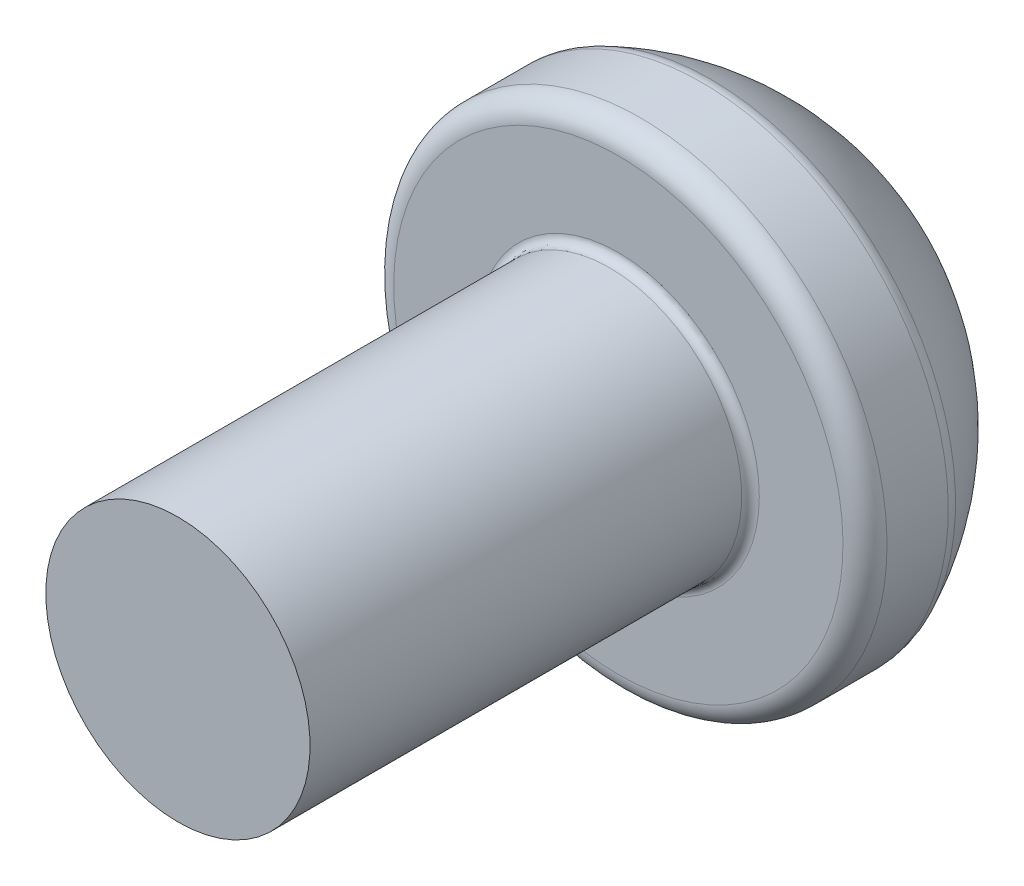
SolidWorks part; units mm, degrees
ref_plane "Plan1" through (0, 0, 0) normal (0, 0, 1) x (1, 0, 0)
ref_plane "Plan2" through (0, 0, 0) normal (0, 1, 0) x (1, 0, 0)
ref_plane "Plan3" through (0, 0, 0) normal (1, 0, 0) x (0, 0, -1)
sketch "Sketch1" plane through (0, 0, 0) normal (1, 0, 0) x (0, 0, -1)
  line L0 (2.4, 0) -> (-5, 0) construction
  line L1 (-5, 0) -> (-5, 1.5)
  line L2 (-5, 1.5) -> (0, 1.5)
  line L3 (0, 1.5) -> (0, 2.8)
  line L4 (0, 2.8) -> (1, 2.8)
  line L5 (2.4, 0) -> (2.4, 1.54)
  line L6 (2.4, 0) -> (-5, 0)
  line L7 (0, 0) -> (-0.5, 0) construction
  line L8 (0, 0) -> (0, 2.15) construction
  line L9 (0, 0) -> (0, 2.55) construction
  arc A0 (1, 2.8) -> (2.4, 1.54) centre (-0.253, 0) cw
  dimension "D1" = 3.08
  dimension "D" = 3
  dimension "L" = 5
  dimension "D2" = 1
  dimension "K" = 2.4
  dimension "DK" = 5.6
  dimension "P" = 0.5
  dimension "DW" = 5.1
revolve "Base-Revolve" add sketch "Sketch1"
cosmetic thread "Cosmetic_Thread1"
fillet "Fillet1" radius 0.1 1 edges at (0, 1.5, 0)
fillet "Fillet2" radius 0.25 2 edges at (0, 2.8, -1) (0, 2.8, 0)
hole_wizard "Hole1" positions "Sketch3" profile "Sketch2" legacy
sketch "Sketch3" plane through (0, 0, -2.4) normal (0, 0, -1) x (-1, 0, 0)
  circle A0 centre (0, 0) radius 1.54 construction
  point P0 (0, 0)
sketch "Sketch2" plane through (0, 0, -2.4) normal (1, 0, 0) x (0, 1, 0)
  line L0 (0, 0) -> (0, 1.3731)
  line L1 (0, 1.3731) -> (1.025, 1)
  line L2 (1.025, 1) -> (1.025, 0)
  line L4 (1.025, 0) -> (0, 0)
  line L6 (0, 1.3731) -> (-1.025, 1) construction
  line L7 (0, -4.2442) -> (0, 117.3081) construction
  dimension "Diameter" = 2.05
  dimension "Depth" = 1
  dimension "Drill Angle" = 140
sketch "Sketch4" plane through (0, 0, -2.4) normal (0, 0, -1) x (-1, 0, 0)
  line L0 (0, 1.4) -> (0, -1.4) construction
  line L1 (0, 0) -> (0.8075, -1.3986) construction
  line L2 (0, 0) -> (-0.8075, -1.3986) construction
  line L3 (0, 0) -> (-1.615, 0) construction
  line L4 (0, 0) -> (-0.8075, 1.3986) construction
  line L5 (0, 0) -> (0.8075, 1.3986) construction
  line L6 (0, 0) -> (1.615, 0) construction
  arc A0 (1.0888, -0.88) -> (1.3065, -0.5029) centre (0, 0) ccw
  arc A1 (1.0888, -0.88) -> (0.2177, -1.383) centre (0.8075, -1.3986) ccw
  circle A2 centre (0, 0) radius 1.025 construction
  arc A3 (-0.2177, -1.383) -> (-1.0888, -0.88) centre (-0.8075, -1.3986) ccw
  arc A4 (-1.3065, -0.5029) -> (-1.3065, 0.5029) centre (-1.615, 0) ccw
  arc A5 (-1.0888, 0.88) -> (-0.2177, 1.383) centre (-0.8075, 1.3986) ccw
  arc A6 (0.2177, 1.383) -> (1.0888, 0.88) centre (0.8075, 1.3986) ccw
  arc A7 (1.3065, 0.5029) -> (1.3065, -0.5029) centre (1.615, 0) ccw
  arc A8 (1.3065, 0.5029) -> (1.0888, 0.88) centre (0, 0) ccw
  arc A9 (0.2177, 1.383) -> (-0.2177, 1.383) centre (0, 0) ccw
  arc A10 (-1.0888, 0.88) -> (-1.3065, 0.5029) centre (0, 0) ccw
  arc A11 (-1.3065, -0.5029) -> (-1.0888, -0.88) centre (0, 0) ccw
  arc A12 (-0.2177, -1.383) -> (0.2177, -1.383) centre (0, 0) ccw
  dimension "AE" = 2.8
  dimension "EE" = 0.59
  dimension "D2" = 30
  dimension "D4" = 30
  dimension "D5" = 30
  dimension "D6" = 30
extrude "Cut-Extrude1" cut sketch "Sketch4" against normal blind 1
equation "\"D2@Sketch1\" = \"Depth@Sketch2\""
equation "\"D1@Sketch1\" = 1.1*\"AE@Sketch4\""
equation "\"D1@Cosmetic_Thread1\" = \"D@Sketch1\"-(1.0825*\"P@Sketch1\")"
equation "\"D1@Fillet2\" = (\"DK@Sketch1\"-\"DW@Sketch1\")/2"
equation "\"T@Cut-Extrude1\" = \"Depth@Sketch2\""
